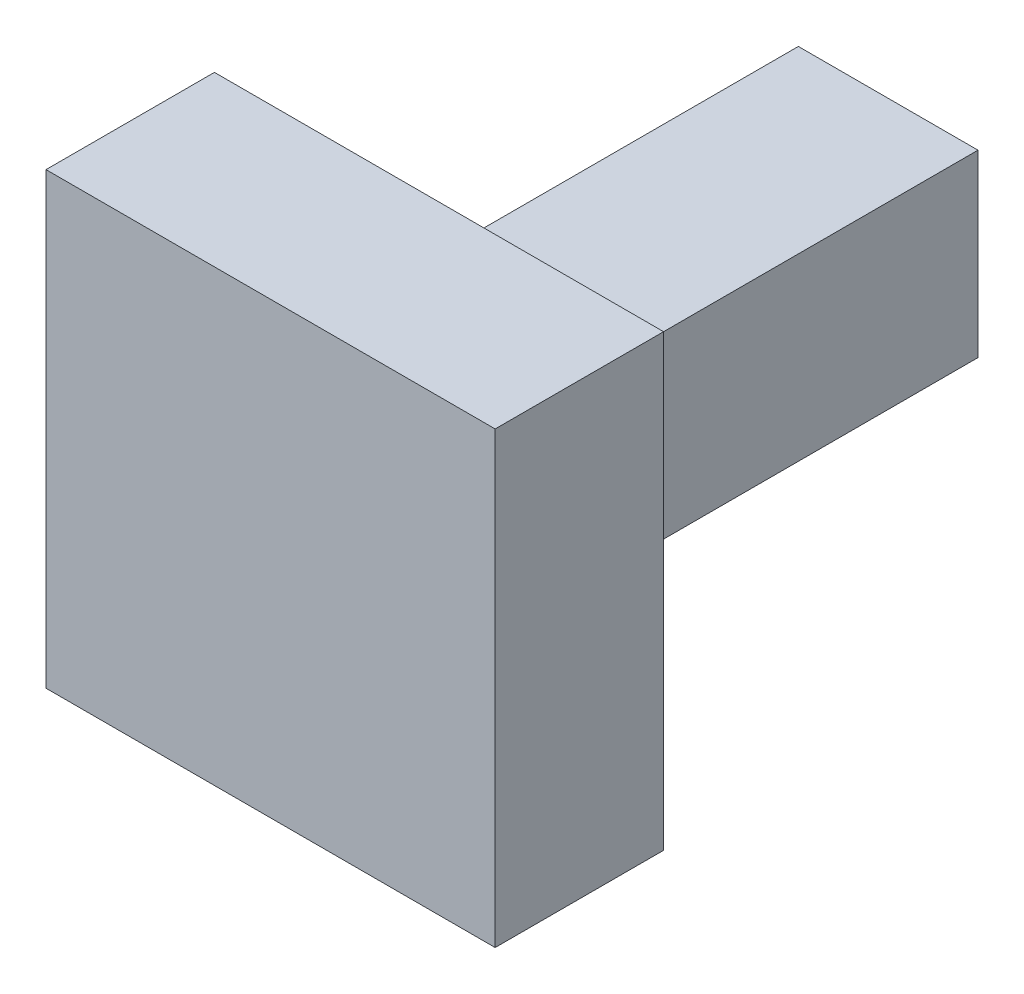
SolidWorks part; units mm, degrees
ref_plane "前视基准面" through (0, 0, 0) normal (0, 0, 1) x (1, 0, 0)
ref_plane "上视基准面" through (0, 0, 0) normal (0, 1, 0) x (1, 0, 0)
ref_plane "右视基准面" through (0, 0, 0) normal (1, 0, 0) x (0, 0, -1)
sketch "草图1" plane through (0, 0, 0) normal (0, 0, 1) x (1, 0, 0)
  line L1 (-8, 8) -> (8, 8)
  line L2 (-8, 8) -> (-8, -8)
  line L3 (-8, -8) -> (8, -8)
  line L4 (8, 8) -> (8, -8)
  line L5 (-8, 8) -> (8, -8) construction
  line L6 (-8, -8) -> (8, 8) construction
  line L11 (-20, 20) -> (20, 20)
  line L12 (-20, 20) -> (-20, -20)
  line L13 (-20, -20) -> (20, -20)
  line L14 (20, 20) -> (20, -20)
  line L15 (-20, 20) -> (20, -20) construction
  line L16 (-20, -20) -> (20, 20) construction
  point P0 (0, 0)
  point P5 (0, 0)
  point P6 (0, 0)
  point P12 (0, 0)
  dimension "D1" = 16
  dimension "D2" = 16
  dimension "D3" = 40
  dimension "D4" = 40
extrude "凸台-拉伸2" add sketch "草图1" along normal blind 15
sketch "草图2" plane through (0, 0, 15) normal (0, 0, 1) x (1, 0, 0)
  line L0 (-8, 8) -> (-8, -8)
  line L1 (-8, -8) -> (8, -8)
  line L2 (8, -8) -> (8, 8)
  line L3 (8, 8) -> (-8, 8)
extrude "凸台-拉伸3" add sketch "草图2" against normal blind 55
